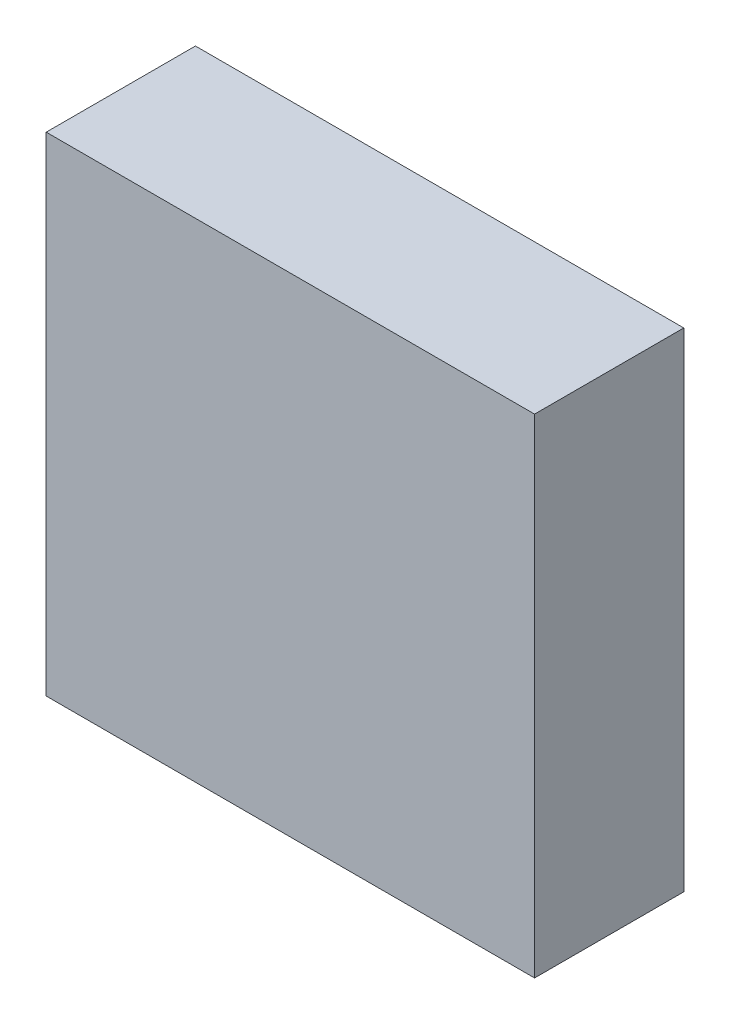
SolidWorks part; units mm, degrees
ref_plane "前视基准面" through (0, 0, 0) normal (0, 0, 1) x (1, 0, 0)
ref_plane "上视基准面" through (0, 0, 0) normal (0, 1, 0) x (1, 0, 0)
ref_plane "右视基准面" through (0, 0, 0) normal (1, 0, 0) x (0, 0, -1)
other "Configuration Table"
sketch "草图1" plane through (0, 0, 0) normal (0, 0, 1) x (1, 0, 0)
  line L1 (-18, 18) -> (18, 18)
  line L2 (-18, 18) -> (-18, -18)
  line L3 (-18, -18) -> (18, -18)
  line L4 (18, 18) -> (18, -18)
  line L5 (-18, 18) -> (18, -18) construction
  line L6 (-18, -18) -> (18, 18) construction
  point P0 (0, 0)
  dimension "D1" = 36
extrude "凸台-拉伸1" add sketch "草图1" along normal blind 11
sketch "草图2" plane through (0, 0, 11) normal (0, 0, 1) x (1, 0, 0)
  line L1 (-4.6008, 4.6008) -> (4.6008, 4.6008)
  line L2 (-4.6008, 4.6008) -> (-4.6008, -4.6008)
  line L3 (-4.6008, -4.6008) -> (4.6008, -4.6008)
  line L4 (4.6008, 4.6008) -> (4.6008, -4.6008)
  line L5 (-4.6008, 4.6008) -> (4.6008, -4.6008) construction
  line L6 (-4.6008, -4.6008) -> (4.6008, 4.6008) construction
  point P0 (0, 0)
